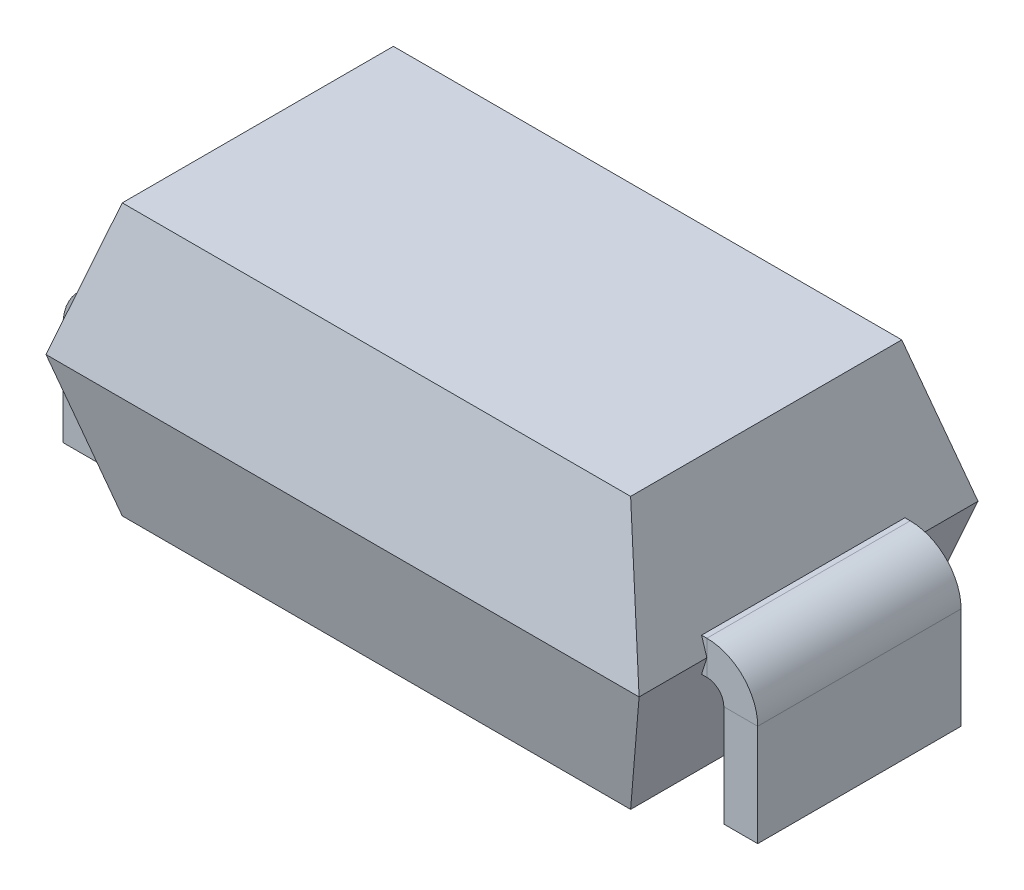
SolidWorks part; units mm, degrees
ref_plane "Front Plane" through (0, 0, 0) normal (0, 0, 1) x (1, 0, 0)
ref_plane "Top Plane" through (0, 0, 0) normal (0, 1, 0) x (1, 0, 0)
ref_plane "Right Plane" through (0, 0, 0) normal (1, 0, 0) x (0, 0, -1)
sketch "Base" plane through (0, 0, 0) normal (0, 1, 0) x (1, 0, 0)
  line L1 (-1.75, 1) -> (1.75, 1)
  line L2 (-1.75, 1) -> (-1.75, -1)
  line L3 (-1.75, -1) -> (1.75, -1)
  line L4 (1.75, 1) -> (1.75, -1)
  line L5 (-1.75, 1) -> (1.75, -1) construction
  line L6 (-1.75, -1) -> (1.75, 1) construction
  point P0 (0, 0)
  dimension "D1" = 2
  dimension "D2" = 3.5
ref_plane "TopRP" through (0, 0.8, 0) normal (0, 1, 0) x (1, 0, 0)
sketch "Top" plane through (0, 0.8, 0) normal (0, 1, 0) x (1, 0, 0)
  line L0 (-1.75, 1) -> (-1.75, -1) construction
  line L1 (-1.5, 0.8) -> (1.5, 0.8)
  line L2 (-1.5, 0.8) -> (-1.5, -0.8)
  line L3 (-1.5, -0.8) -> (1.5, -0.8)
  line L4 (1.5, 0.8) -> (1.5, -0.8)
  line L5 (-1.5, 0.8) -> (1.5, -0.8) construction
  line L6 (-1.5, -0.8) -> (1.5, 0.8) construction
  line L7 (-1.75, 1) -> (1.75, 1) construction
  point P0 (0, 0)
  dimension "D1" = 0.25
  dimension "D2" = 0.2
loft "Loft1" add profiles "Base", "Top"
mirror "Mirror1" about plane through (0, 0, 0) normal (0, 1, 0) of "Loft1"
sketch "RefP" plane through (0, 0, 0) normal (0, 0, 1) x (1, 0, 0)
  line L0 (-1.75, 0) -> (1.75, 0) construction
  point P0 (1.55, 0)
  dimension "D1" = 0.2
ref_plane "LegP" through (1.55, 0, 0) normal (1, 0, 0) x (0, 0, -1)
sketch "Sketch3" plane through (0, 0, 0) normal (0, 0, 1) x (1, 0, 0)
  line L0 (1.55, 0) -> (1.75, 0)
  line L1 (1.95, -0.2) -> (1.95, -0.8)
  line L2 (1.95, -0.8) -> (1.5, -0.8) construction
  arc A0 (1.75, 0) -> (1.95, -0.2) centre (1.75, -0.2) cw
  dimension "D1" = 0.2
sketch "Sketch4" plane through (1.55, 0, 0) normal (1, 0, 0) x (0, 0, -1)
  line L1 (0.6, 0.1) -> (-0.6, 0.1)
  line L2 (0.6, 0.1) -> (0.6, -0.1)
  line L3 (0.6, -0.1) -> (-0.6, -0.1)
  line L4 (-0.6, 0.1) -> (-0.6, -0.1)
  line L5 (0.6, 0.1) -> (-0.6, -0.1) construction
  line L6 (0.6, -0.1) -> (-0.6, 0.1) construction
  point P0 (0, 0)
  dimension "Height" = 0.2
  dimension "Width" = 1.2
sweep "Sweep1" add profiles "Sketch4" path "Sketch3"
mirror "Mirror3" about plane through (0, 0, 0) normal (1, 0, 0) of "Sweep1"
